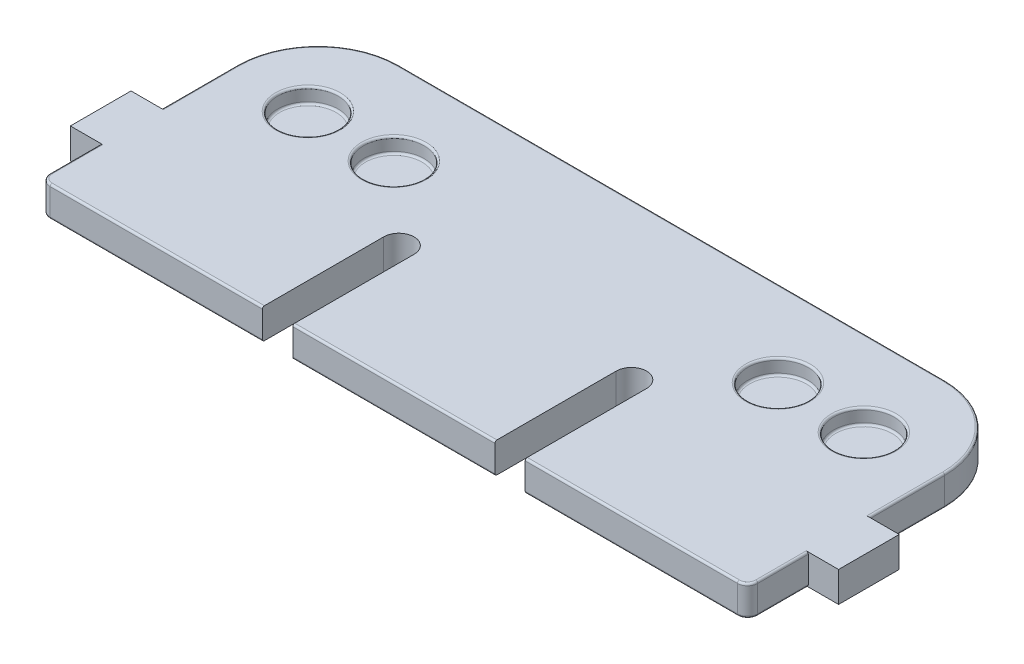
SolidWorks part; units mm, degrees
ref_plane "Front Plane" through (0, 0, 0) normal (0, 0, 1) x (1, 0, 0)
ref_plane "Top Plane" through (0, 0, 0) normal (0, 1, 0) x (1, 0, 0)
ref_plane "Right Plane" through (0, 0, 0) normal (1, 0, 0) x (0, 0, -1)
sketch "Sketch1" plane through (0, 0, 0) normal (0, 1, 0) x (1, 0, 0)
  line L0 (-10, 12) -> (-10, 0)
  line L1 (-10, 0) -> (10, 0)
  line L2 (-13, 12) -> (-13, 0)
  line L3 (-13, 0) -> (-34, 0)
  line L4 (-35, 1) -> (-35, 6)
  line L5 (-35, 6) -> (-38, 6)
  line L6 (-38, 6) -> (-38, 12)
  line L7 (-38, 12) -> (-35, 12)
  line L8 (-35, 12) -> (-35, 19.5)
  line L9 (-27, 27.5) -> (27, 27.5)
  line L10 (0, 0) -> (0, 27.5) construction
  line L11 (35, 12) -> (35, 19.5)
  line L12 (38, 12) -> (35, 12)
  line L13 (38, 6) -> (38, 12)
  line L14 (35, 6) -> (38, 6)
  line L15 (35, 1) -> (35, 6)
  line L16 (13, 0) -> (34, 0)
  line L17 (13, 12) -> (13, 0)
  line L18 (10, 12) -> (10, 0)
  arc A0 (-10, 12) -> (-13, 12) centre (-11.5, 12) ccw
  arc A1 (-35, 19.5) -> (-27, 27.5) centre (-27, 19.5) cw
  arc A2 (35, 19.5) -> (27, 27.5) centre (27, 19.5) ccw
  arc A3 (10, 12) -> (13, 12) centre (11.5, 12) cw
  arc A4 (35, 1) -> (34, 0) centre (34, 1) cw
  arc A5 (-34, 0) -> (-35, 1) centre (-34, 1) cw
  point P31 (35, 0)
  point P34 (-35, 0)
  dimension "D1" = 1.5
  dimension "D9" = 8
  dimension "D10" = 1
  dimension "D2" = 10
  dimension "D3" = 27.5
  dimension "D4" = 12
  dimension "D5" = 35
  dimension "D6" = 3
  dimension "D7" = 6
  dimension "D8" = 6
extrude "Boss-Extrude1" add sketch "Sketch1" along normal blind 3
sketch "Sketch2" plane through (0, 3, 0) normal (0, 1, 0) x (1, 0, 0)
  line L0 (0, 0) -> (0, 27.5) construction
  line L1 (27, 27.5) -> (-27, 27.5) construction
  line L2 (-34, 0) -> (-13, 0) construction
  circle A0 centre (-27.5, 19) radius 3
  circle A1 centre (-19, 19) radius 3
  circle A2 centre (19, 19) radius 3
  circle A3 centre (27.5, 19) radius 3
  dimension "D1" = 6
  dimension "D2" = 6
  dimension "D3" = 8.5
  dimension "D4" = 19
  dimension "D5" = 19
extrude "Cut-Extrude1" cut sketch "Sketch2" against normal blind 1.5
fillet "Fillet1" radius 0.2 32 edges at (23.5, 0, 0) (34.7071, 0, -0.2929) (23.5, 3, 0) (34.7071, 3, -0.2929) (35, 0, -15.75) (-35, 0, -15.75) (-32.6569, 0, -25.1569) (0, 0, -27.5) (35, 3, -15.75) (32.6569, 3, -25.1569) (0, 3, -27.5) (-32.6569, 3, -25.1569) (-35, 0, -3.5) (-34.7071, 0, -0.2929) (-35, 3, -3.5) (-34.7071, 3, -0.2929) (27.5, 3, -22) (27.5, 1.5, -22) (19, 3, -22) (19, 1.5, -22) (-27.5, 1.5, -16) (-19, 3, -16) (-19, 1.5, -16) (-27.5, 3, -16) (0, 0, 0) (0, 3, 0) (35, 0, -3.5) (35, 3, -3.5) (32.6569, 0, -25.1569) (-35, 3, -15.75) (-23.5, 0, 0) (-23.5, 3, 0)
ref_plane "Plane1" through (0, 0, -12) normal (0, 0, 1) x (0, -1, 0)
